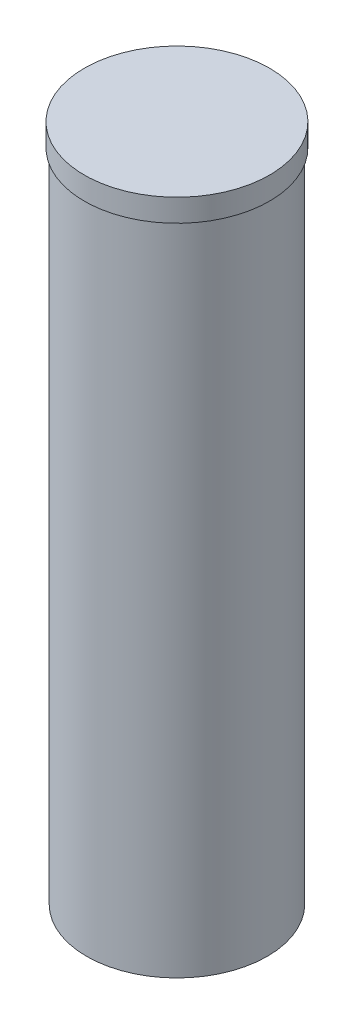
SolidWorks part; units mm, degrees
ref_plane "前视基准面" through (0, 0, 0) normal (0, 0, 1) x (1, 0, 0)
ref_plane "上视基准面" through (0, 0, 0) normal (0, 1, 0) x (1, 0, 0)
ref_plane "右视基准面" through (0, 0, 0) normal (1, 0, 0) x (0, 0, -1)
other "Configuration Table"
sketch "草图1" plane through (0, 0, 0) normal (0, 0, 1) x (1, 0, 0)
  line L1 (0, 0) -> (20, 0)
  line L2 (0, 0) -> (0, 150)
  line L3 (0, 150) -> (20, 150)
  line L4 (20, 0) -> (20, 150)
  line L9 (20, 150) -> (20.5, 150)
  line L10 (20, 150) -> (20, 145)
  line L11 (20, 145) -> (20.5, 145)
  line L12 (20.5, 150) -> (20.5, 145)
  circle A0 centre (0, -47.423) radius 9.4718
  dimension "D1" = 20
  dimension "D2" = 5
  dimension "D3" = 0.5
revolve "旋转2" add sketch "草图1" angle 360 about L2
sketch "草图6" plane through (0, 0, 0) normal (0, -1, 0) x (1, 0, 0)
  circle A0 centre (46.3941, 20.4039) radius 10.6117
